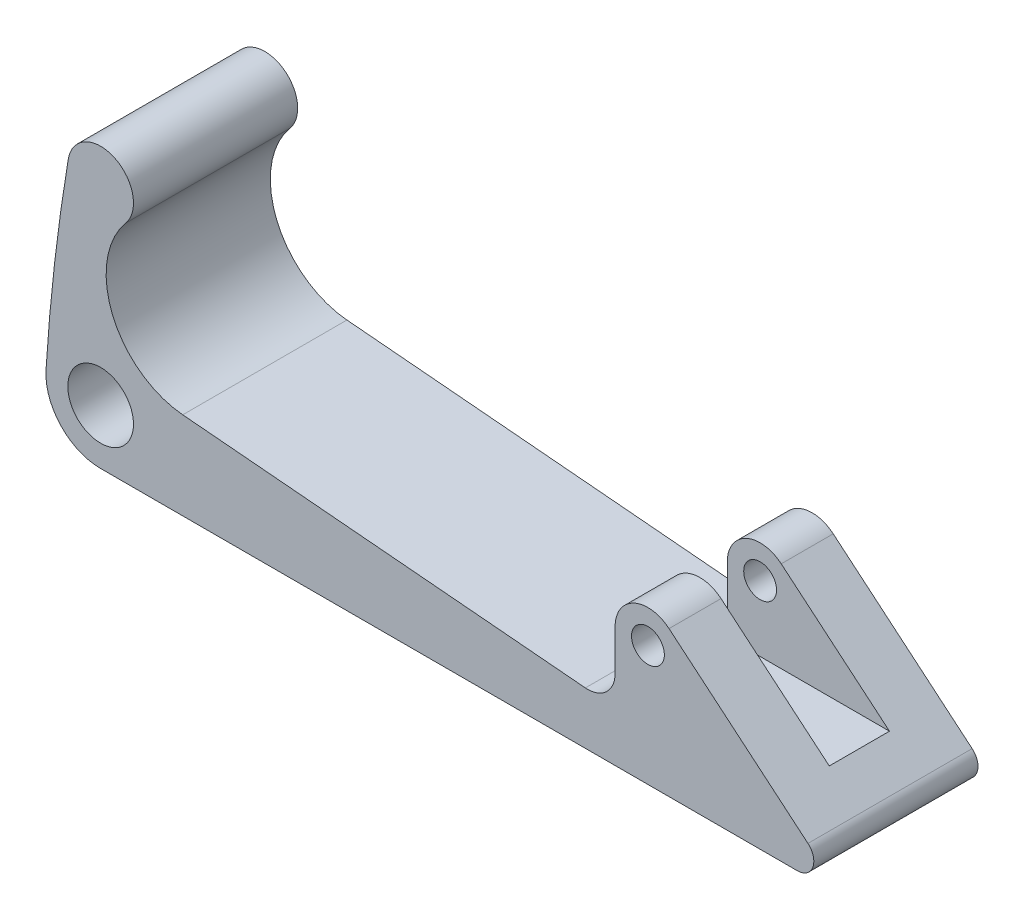
SolidWorks part; units mm, degrees
material "1.0060 (E335)"
ref_plane "Front Plane" through (0, 0, 0) normal (0, 0, 1) x (1, 0, 0)
ref_plane "Top Plane" through (0, 0, 0) normal (0, 1, 0) x (1, 0, 0)
ref_plane "Right Plane" through (0, 0, 0) normal (1, 0, 0) x (0, 0, -1)
sketch "Sketch1" plane through (0, 0, 0) normal (0, 0, 1) x (1, 0, 0)
  line L1 (0, -5) -> (63.6552, -5)
  line L2 (64.6194, -2.3509) -> (51.9284, 8.2981)
  line L3 (47, 6) -> (47, 2.2725)
  line L4 (44.2821, -0.218) -> (7.5, 3)
  line L6 (7.5, 3) -> (7.5, -5) construction
  line L7 (75.7111, -2.9677) -> (49885.446, -4360.7548) construction
  circle A0 centre (0, 0) radius 3
  arc A1 (-2.9584, 17.998) -> (2.2971, 15.5704) centre (0, 17.5) cw
  arc A3 (63.6552, -5) -> (64.6194, -2.3509) centre (63.6552, -3.5) ccw
  arc A4 (51.9284, 8.2981) -> (47, 6) centre (50, 6) ccw
  arc A5 (47, 2.2725) -> (44.2821, -0.218) centre (44.5, 2.2725) cw
  arc A6 (2.2971, 15.5704) -> (7.5, 3) centre (8.1683, 10.6385) ccw
  arc A8 (0, -5) -> (-4.9904, 0.3097) centre (0, 0) cw
  arc A9 (-4.9904, 0.3097) -> (-2.9584, 17.998) centre (164.6831, -10.2214) cw
  circle A10 centre (50, 6) radius 1.5
  point P4 (3, 17.5)
  point P20 (50, 9)
  point P21 (50, -0.7183)
  point P23 (65.1552, -3.5)
  point P28 (-5, 0)
  dimension "D1" = 50
  dimension "D2" = 1.5
  dimension "D3" = 3
  dimension "D4" = 2.5
  dimension "D5" = 6
  dimension "D10" = 170
  dimension "D11" = 3
  dimension "D12" = 5
  dimension "D17" = 3
  dimension "D6" = 17.5
  dimension "D7" = 42.5
  dimension "D8" = 8
  dimension "D9" = 5
  dimension "D13" = 14
  dimension "D14" = 40
  dimension "D15" = 4.2817
  dimension "D16" = 70.1552
extrude "Boss-Extrude1" add sketch "Sketch1" along normal mid plane 15
ref_plane "Plane1" through (0, 2.5, 0) normal (0, 1, 0) x (1, 0, 0)
sketch "Sketch2" plane through (0, 0, 0) normal (0, 1, 0) x (1, 0, 0)
  line L1 (44.2821, 2.75) -> (64.6194, 2.75)
  line L2 (44.2821, 2.75) -> (44.2821, -2.75)
  line L3 (44.2821, -2.75) -> (64.6194, -2.75)
  line L4 (64.6194, 2.75) -> (64.6194, -2.75)
  line L5 (64.6194, -7.5) -> (64.6194, 7.5) construction
  line L6 (44.2821, -7.5) -> (44.2821, 7.5) construction
  point P6 (47, 0)
  dimension "D1" = 5.5
extrude "Cut-Extrude1" cut sketch "Sketch2" along normal up to next contours L1 L4 L3 L2
